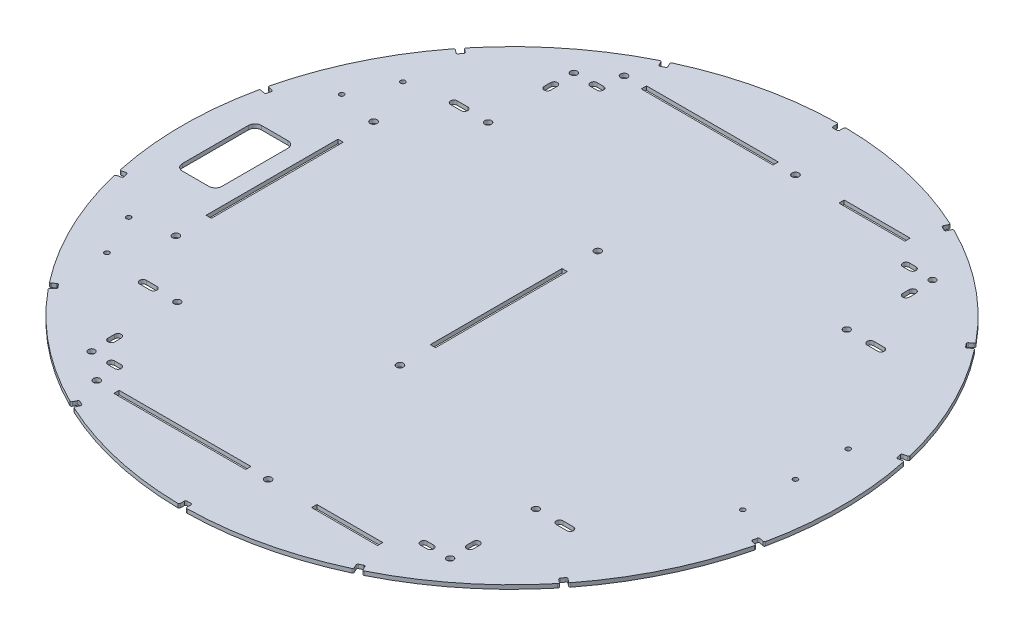
SolidWorks part; units mm, degrees
ref_plane "Front Plane" through (0, 0, 0) normal (0, 0, 1) x (1, 0, 0)
ref_plane "Top Plane" through (0, 0, 0) normal (0, 1, 0) x (1, 0, 0)
ref_plane "Right Plane" through (0, 0, 0) normal (1, 0, 0) x (0, 0, -1)
sketch "Sketch1" plane through (0, 0, 0) normal (0, 1, 0) x (1, 0, 0)
  circle A0 centre (0, 0) radius 250
extrude "Boss-Extrude1" add sketch "Sketch1" along normal blind 3
sketch "Sketch11" plane through (0, 3, 0) normal (0, 1, 0) x (1, 0, 0)
  line L1 (1.5, 245) -> (-1.5, 245)
  line L2 (2.5, 246) -> (2.5, 255)
  line L3 (2.5, 255) -> (-2.5, 255)
  line L4 (-2.5, 246) -> (-2.5, 255)
  line L5 (2.5, 245) -> (-2.5, 255) construction
  line L6 (2.5, 255) -> (-2.5, 245) construction
  circle A0 centre (0, 0) radius 250 construction
  arc A1 (2.5, 246) -> (1.5, 245) centre (1.5, 246) cw
  arc A2 (-1.5, 245) -> (-2.5, 246) centre (-1.5, 246) cw
  point P0 (0, 250)
  dimension "D3" = 1
  dimension "D1" = 10
  dimension "D2" = 5
extrude "Cut-Extrude5" cut sketch "Sketch11" against normal blind 4
fillet "Fillet1" radius 1 2 edges at (2.5, 1.5, -249.9875) (-2.5, 1.5, -249.9875)
pattern_circular "CirPattern1" count 14 over 360 about axis through (0, 0, 0) along (0, 1, 0) of "Cut-Extrude5", "Fillet1"
sketch "Sketch17" plane through (0, 3, 0) normal (0, 1, 0) x (1, 0, 0)
  line L0 (-8, -50) -> (-8, 50)
  line L1 (-182, -50) -> (-178, -50)
  line L2 (-182, -50) -> (-182, 50)
  line L3 (-182, 50) -> (-178, 50)
  line L4 (-178, -50) -> (-178, 50)
  line L5 (-182, -50) -> (-178, 50) construction
  line L6 (-182, 50) -> (-178, -50) construction
  line L7 (-12, 50) -> (-8, 50)
  line L8 (-12, -50) -> (-12, 50)
  line L9 (-12, -50) -> (-8, -50)
  point P0 (-180, 0)
  dimension "D1" = 100
  dimension "D2" = 4
  dimension "D3" = 0
  dimension "D4" = 180
  dimension "D5" = 2
extrude "Cut-Extrude11" cut sketch "Sketch17" against normal blind 10
sketch "Sketch18" plane through (0, 3, 0) normal (0, 1, 0) x (1, 0, 0)
  line L0 (-178, -50) -> (-178, 50) construction
  line L1 (-1.65, 0) -> (1.65, 0) construction
  circle A0 centre (-180, 75) radius 2.6
  circle A1 centre (-180, -75) radius 2.6
  circle A2 centre (-10, 75) radius 2.6
  circle A3 centre (-10, -75) radius 2.6
  point P4 (-178, 0)
  dimension "D1" = 75
  dimension "D2" = 2
extrude "Cut-Extrude12" cut sketch "Sketch18" against normal blind 10
sketch "Sketch20" plane through (0, 0, 0) normal (0, -1, 0) x (1, 0, 0)
  line L0 (-166.5, -117.9) -> (-148.647, -117.9) construction
  line L1 (-162, -117.9) -> (-154, -117.9) construction
  line L2 (-162, -115.4) -> (-154, -115.4)
  line L3 (-162, -120.4) -> (-154, -120.4)
  line L4 (0, -1.65) -> (0, 1.65) construction
  line L5 (166.5, -117.9) -> (148.647, -117.9) construction
  line L6 (162, -117.9) -> (154, -117.9) construction
  line L7 (162, -115.4) -> (154, -115.4)
  line L8 (162, -120.4) -> (154, -120.4)
  line L9 (1.65, 0) -> (-1.65, 0) construction
  line L10 (162, 117.9) -> (154, 117.9) construction
  line L11 (162, 115.4) -> (154, 115.4)
  line L12 (162, 120.4) -> (154, 120.4)
  line L13 (-162, 117.9) -> (-154, 117.9) construction
  line L14 (-162, 115.4) -> (-154, 115.4)
  line L15 (-162, 120.4) -> (-154, 120.4)
  line L16 (-166.5, 117.9) -> (-148.647, 117.9) construction
  line L17 (166.5, 117.9) -> (148.647, 117.9) construction
  arc A0 (-164, -115.4) -> (-164, -120.4) centre (-164, -117.9) ccw construction
  arc A1 (-162, -115.4) -> (-162, -120.4) centre (-162, -117.9) ccw
  arc A2 (-154, -120.4) -> (-154, -115.4) centre (-154, -117.9) ccw
  arc A3 (162, -115.4) -> (162, -120.4) centre (162, -117.9) cw
  arc A4 (154, -120.4) -> (154, -115.4) centre (154, -117.9) cw
  arc A5 (162, 115.4) -> (162, 120.4) centre (162, 117.9) ccw
  arc A6 (154, 120.4) -> (154, 115.4) centre (154, 117.9) ccw
  arc A7 (-162, 115.4) -> (-162, 120.4) centre (-162, 117.9) cw
  arc A8 (-154, 120.4) -> (-154, 115.4) centre (-154, 117.9) cw
  point P8 (-158, -117.9)
  point P20 (158, -117.9)
  point P29 (158, 117.9)
  point P36 (-158, 117.9)
  dimension "D1" = 2.5
  dimension "D2" = 8
  dimension "D3" = 158
extrude "Cut-Extrude14" cut sketch "Sketch20" against normal blind 14
sketch "Sketch21" plane through (0, 3, 0) normal (0, 1, 0) x (1, 0, 0)
  line L0 (-1.65, 0) -> (1.65, 0) construction
  line L1 (0, 198) -> (-100, 198)
  line L2 (0, 198) -> (0, 202)
  line L3 (0, 202) -> (-100, 202)
  line L4 (-100, 198) -> (-100, 202)
  line L5 (0, 198) -> (-100, 202) construction
  line L6 (0, 202) -> (-100, 198) construction
  line L7 (0, -202) -> (-100, -198) construction
  line L8 (0, -198) -> (-100, -202) construction
  line L9 (-100, -198) -> (-100, -202)
  line L10 (0, -202) -> (-100, -202)
  line L11 (0, -198) -> (0, -202)
  line L12 (0, -198) -> (-100, -198)
  circle A0 centre (-115, 200) radius 2.6
  circle A1 centre (15, 200) radius 2.6
  circle A2 centre (15, -200) radius 2.6
  circle A3 centre (-115, -200) radius 2.6
  point P0 (-50, 200)
  point P13 (-50, -200)
  dimension "D5" = 65
  dimension "D6" = 65
  dimension "D1" = 4
  dimension "D2" = 100
  dimension "D3" = 200
  dimension "D4" = 50
extrude "Cut-Extrude15" cut sketch "Sketch21" against normal blind 14
sketch "Sketch22" plane through (0, 3, 0) normal (0, 1, 0) x (1, 0, 0)
  line L0 (-1.65, 0) -> (1.65, 0) construction
  line L1 (0, -1.65) -> (0, 1.65) construction
  circle A0 centre (-136, -117.9) radius 2.5
  circle A1 centre (-136, 117.9) radius 2.5
  circle A2 centre (136, 117.9) radius 2.5
  circle A3 centre (136, -117.9) radius 2.5
  circle A4 centre (-136, 182.9) radius 2.5
  circle A5 centre (136, 182.9) radius 2.5
  circle A6 centre (-136, -182.9) radius 2.5
  circle A7 centre (136, -182.9) radius 2.5
  dimension "D1" = 2
extrude "Cut-Extrude16" cut sketch "Sketch22" against normal blind 14
sketch "Sketch24" plane through (0, 0, 0) normal (0, -1, 0) x (1, 0, 0)
  line L1 (-200, -30) -> (-220, -30)
  line L2 (-195, -25) -> (-195, 25)
  line L3 (-200, 30) -> (-220, 30)
  line L4 (-225, -25) -> (-225, 25)
  line L5 (-195, -30) -> (-225, 30) construction
  line L6 (-195, 30) -> (-225, -30) construction
  arc A0 (-195, -25) -> (-200, -30) centre (-200, -25) cw
  arc A1 (-220, -30) -> (-225, -25) centre (-220, -25) cw
  arc A2 (-195, 25) -> (-200, 30) centre (-200, 25) ccw
  arc A3 (-225, 25) -> (-220, 30) centre (-220, 25) cw
  point P0 (-210, 0)
  dimension "D1" = 5
extrude "Cut-Extrude17" cut sketch "Sketch24" against normal blind 14
sketch "Sketch25" plane through (0, 3, 0) normal (0, 1, 0) x (1, 0, 0)
  line L1 (50, 202) -> (100, 202)
  line L2 (50, 202) -> (50, 198)
  line L3 (50, 198) -> (100, 198)
  line L4 (100, 202) -> (100, 198)
  line L5 (50, -198) -> (100, -198)
  line L6 (50, -198) -> (50, -202)
  line L7 (50, -202) -> (100, -202)
  line L8 (100, -198) -> (100, -202)
extrude "Cut-Extrude18" cut sketch "Sketch25" against normal blind 4
sketch "Sketch26" plane through (0, 3, 0) normal (0, 1, 0) x (1, 0, 0)
  line L0 (-136, 162.9) -> (-136, 167.9) construction
  line L1 (-138.5, 162.9) -> (-138.5, 167.9)
  line L2 (-133.5, 162.9) -> (-133.5, 167.9)
  line L3 (-116, 182.9) -> (-121, 182.9) construction
  line L4 (-116, 180.4) -> (-121, 180.4)
  line L5 (-116, 185.4) -> (-121, 185.4)
  line L6 (0, -1.65) -> (0, 1.65) construction
  line L7 (116, 182.9) -> (121, 182.9) construction
  line L8 (116, 180.4) -> (121, 180.4)
  line L9 (116, 185.4) -> (121, 185.4)
  line L10 (136, 162.9) -> (136, 167.9) construction
  line L11 (138.5, 162.9) -> (138.5, 167.9)
  line L12 (133.5, 162.9) -> (133.5, 167.9)
  line L13 (-1.65, 0) -> (1.65, 0) construction
  line L14 (116, -182.9) -> (121, -182.9) construction
  line L15 (116, -180.4) -> (121, -180.4)
  line L16 (116, -185.4) -> (121, -185.4)
  line L17 (136, -162.9) -> (136, -167.9) construction
  line L18 (138.5, -162.9) -> (138.5, -167.9)
  line L19 (133.5, -162.9) -> (133.5, -167.9)
  line L20 (-136, -162.9) -> (-136, -167.9) construction
  line L21 (-138.5, -162.9) -> (-138.5, -167.9)
  line L22 (-133.5, -162.9) -> (-133.5, -167.9)
  line L23 (-116, -182.9) -> (-121, -182.9) construction
  line L24 (-116, -180.4) -> (-121, -180.4)
  line L25 (-116, -185.4) -> (-121, -185.4)
  arc A0 (-138.5, 162.9) -> (-133.5, 162.9) centre (-136, 162.9) ccw
  arc A1 (-133.5, 167.9) -> (-138.5, 167.9) centre (-136, 167.9) ccw
  circle A2 centre (-136, 182.9) radius 2.5 construction
  arc A3 (-116, 180.4) -> (-116, 185.4) centre (-116, 182.9) ccw
  arc A4 (-121, 185.4) -> (-121, 180.4) centre (-121, 182.9) ccw
  arc A5 (116, 180.4) -> (116, 185.4) centre (116, 182.9) cw
  arc A6 (121, 185.4) -> (121, 180.4) centre (121, 182.9) cw
  arc A7 (138.5, 162.9) -> (133.5, 162.9) centre (136, 162.9) cw
  arc A8 (133.5, 167.9) -> (138.5, 167.9) centre (136, 167.9) cw
  arc A9 (116, -180.4) -> (116, -185.4) centre (116, -182.9) ccw
  arc A10 (121, -185.4) -> (121, -180.4) centre (121, -182.9) ccw
  arc A11 (138.5, -162.9) -> (133.5, -162.9) centre (136, -162.9) ccw
  arc A12 (133.5, -167.9) -> (138.5, -167.9) centre (136, -167.9) ccw
  arc A13 (-138.5, -162.9) -> (-133.5, -162.9) centre (-136, -162.9) cw
  arc A14 (-133.5, -167.9) -> (-138.5, -167.9) centre (-136, -167.9) cw
  arc A15 (-116, -180.4) -> (-116, -185.4) centre (-116, -182.9) cw
  arc A16 (-121, -185.4) -> (-121, -180.4) centre (-121, -182.9) cw
  point P3 (-136, 165.4)
  point P12 (-118.5, 182.9)
  point P21 (118.5, 182.9)
  point P28 (136, 165.4)
  point P37 (118.5, -182.9)
  point P44 (136, -165.4)
  point P51 (-136, -165.4)
  point P58 (-118.5, -182.9)
  dimension "D1" = 2.5
  dimension "D4" = 2.5
  dimension "D2" = 5
  dimension "D3" = 17.5
  dimension "D5" = 5
  dimension "D6" = 17.5
extrude "Cut-Extrude19" cut sketch "Sketch26" against normal blind 4
sketch "Sketch27" plane through (0, 3, 0) normal (0, 1, 0) x (1, 0, 0)
  circle A0 centre (215, 0) radius 1.8
  circle A2 centre (215, 40) radius 1.8
  circle A3 centre (215, -40) radius 1.8
  dimension "D1" = 2
  dimension "D3" = 215
  dimension "D2" = 2
extrude "Cut-Extrude20" cut sketch "Sketch27" against normal blind 10
sketch "Sketch28" plane through (0, 3, 0) normal (0, 1, 0) x (1, 0, 0)
  line L0 (-200, 30) -> (-220, 30) construction
  line L1 (-1.65, 0) -> (1.65, 0) construction
  circle A0 centre (-210, 80.7775) radius 1.8
  circle A2 centre (0, 0) radius 225
  circle A3 centre (-195, 112.2497) radius 1.8
  circle A4 centre (-195, -112.2497) radius 1.8
  circle A5 centre (-210, -80.7775) radius 1.8
  point P6 (-210, 30)
  dimension "D1" = 15
  dimension "D2" = 0
  dimension "D3" = 450
extrude "Cut-Extrude21" cut sketch "Sketch28" against normal blind 10 contours A2 A3 | A2 A3 | A2 A0 | A0 A2 | A5 | A4
